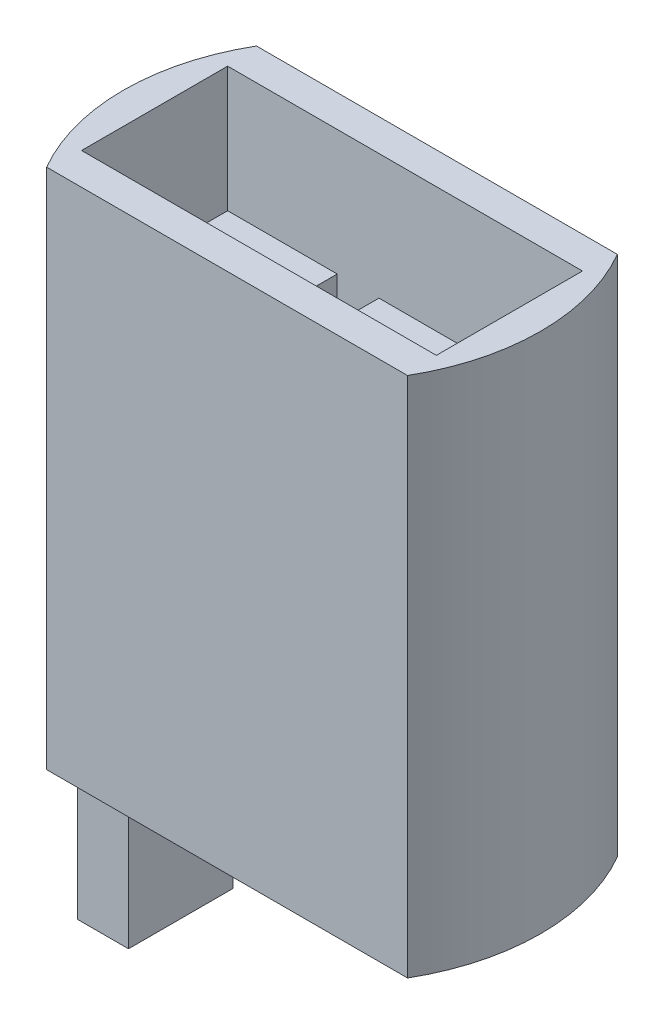
SolidWorks part; units mm, degrees
ref_plane "Front Plane" through (0, 0, 0) normal (0, 0, 1) x (1, 0, 0)
ref_plane "Top Plane" through (0, 0, 0) normal (0, 1, 0) x (1, 0, 0)
ref_plane "Right Plane" through (0, 0, 0) normal (1, 0, 0) x (0, 0, -1)
sketch "Sketch1" plane through (0, 0, 0) normal (0, 1, 0) x (1, 0, 0)
  circle A0 centre (0, 0) radius 10
  dimension "D1" = 20
extrude "Boss-Extrude1" add sketch "Sketch1" along normal blind 25
sketch "Sketch2" plane through (0, 0, 0) normal (0, -1, 0) x (-1, 0, 0)
  line L1 (8.5, 2.5) -> (7.25, 2.5)
  line L2 (8.5, 2.5) -> (8.5, -2.5)
  line L3 (8.5, -2.5) -> (7.25, -2.5)
  line L4 (7.25, 2.5) -> (7.25, -2.5)
  point P4 (7.25, 0)
  dimension "D1" = 5
  dimension "D2" = 1.25
  dimension "D3" = 7.25
extrude "Boss-Extrude2" add sketch "Sketch2" along normal blind 8 separate body
sketch "Sketch3" plane through (-8.5, 0, 0) normal (-1, 0, 0) x (0, 0, 1)
  line L0 (-2.5, -8) -> (-2.5, 0)
  line L1 (-2.5, 0) -> (2.5, 0)
  line L2 (2.5, 0) -> (2.5, -8)
  line L3 (2.5, -8) -> (1.5, -8)
  line L4 (2.5, -8) -> (-2.5, -8) construction
  line L5 (1.5, -8) -> (1.5, -0.75)
  line L6 (1.5, -0.75) -> (-1.5, -0.75)
  line L7 (-1.5, -0.75) -> (-1.5, -8)
  line L8 (-1.5, -8) -> (-2.5, -8)
  dimension "D1" = 1
  dimension "D2" = 1
  dimension "D3" = 0.75
extrude "Boss-Extrude3" add sketch "Sketch3" along normal blind 1.2
sketch "Sketch4" plane through (0, 25, 0) normal (0, 1, 0) x (1, 0, 0)
  line L0 (-10, 0) -> (10, 0) construction
  line L1 (-8.5, -3.5) -> (8.5, -3.5)
  line L2 (-8.5, -3.5) -> (-8.5, 3.5)
  line L3 (-8.5, 3.5) -> (8.5, 3.5)
  line L4 (8.5, -3.5) -> (8.5, 3.5)
  circle A0 centre (0, 0) radius 10 construction
  point P9 (-8.5, 0)
  dimension "D1" = 7
  dimension "D2" = 17
  dimension "D3" = 1.5
extrude "Cut-Extrude1" cut sketch "Sketch4" against normal blind 6
sketch "Sketch5" plane through (0, 19, 0) normal (0, 1, 0) x (1, 0, 0)
  line L0 (8.5, 0) -> (-1.25, 0) construction
  line L1 (8.5, -3.5) -> (8.5, 3.5) construction
  line L2 (8.5, 3.5) -> (-8.5, 3.5) construction
  line L3 (-1.25, 3.5) -> (-3.25, 3.5)
  line L4 (-1.25, 3.5) -> (-1.25, -3.5)
  line L5 (-1.25, -3.5) -> (-3.25, -3.5)
  line L6 (-3.25, 3.5) -> (-3.25, -3.5)
  line L7 (-8.5, -3.5) -> (8.5, -3.5) construction
  dimension "D1" = 9.75
  dimension "D2" = 2
extrude "Cut-Extrude2" cut sketch "Sketch5" against normal blind 4
sketch "Sketch6" plane through (0, 0, 0) normal (0, -1, 0) x (1, 0, 0)
  line L0 (-8.6446, 5.027) -> (8.6446, 5.027)
  line L1 (0, 0) -> (10, 0) construction
  line L2 (10, 0) -> (-10, 0) construction
  line L3 (-8.6446, -5.027) -> (8.6446, -5.027)
  arc A0 (-8.6446, 5.027) -> (8.6446, 5.027) centre (0, 0) cw
  circle A1 centre (0, 0) radius 10 construction
  circle A2 centre (0, 0) radius 10 construction
  arc A3 (-8.6446, -5.027) -> (8.6446, -5.027) centre (0, 0) ccw
  dimension "D1" = 8.6446
extrude "Cut-Extrude3" cut sketch "Sketch6" against normal blind 25
